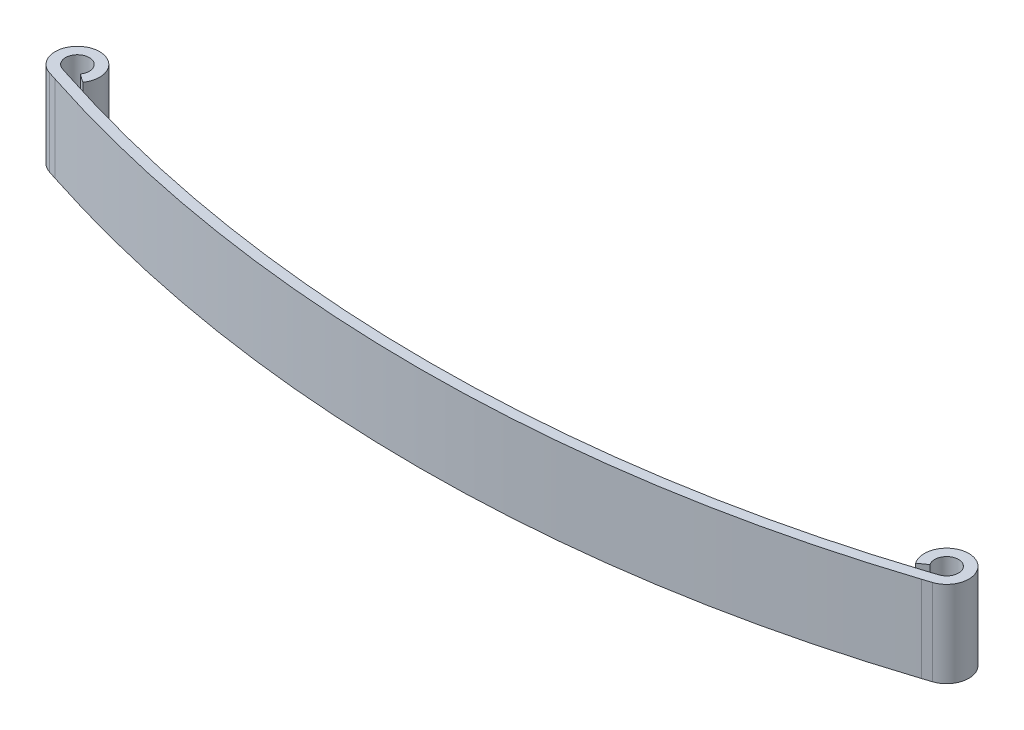
SolidWorks part; units mm, degrees
material "51 Si 7"
ref_plane "Ön Düzlem" through (0, 0, 0) normal (0, 0, 1) x (1, 0, 0)
ref_plane "Üst Düzlem" through (0, 0, 0) normal (0, 1, 0) x (1, 0, 0)
ref_plane "Sağ Düzlem" through (0, 0, 0) normal (1, 0, 0) x (0, 0, -1)
sketch "Sketch1" plane through (0, 0, 0) normal (0, 1, 0) x (1, 0, 0)
  line L0 (721.4563, -1539.3183) -> (730.9671, -1536.229)
  line L2 (725.1634, -1550.7313) -> (734.6743, -1547.642)
  line L4 (715.3996, -1531.0449) -> (705.5901, -1537.9567)
  line L5 (-282.2509, -1550.7313) -> (-291.7618, -1547.642)
  line L6 (-272.4871, -1531.0449) -> (-262.6775, -1537.9567)
  line L7 (-278.5437, -1539.3183) -> (-288.0546, -1536.229)
  arc A0 (-278.5437, -1539.3183) -> (721.4563, -1539.3183) centre (221.4563, 0) ccw
  arc A1 (-282.2509, -1550.7313) -> (725.1634, -1550.7313) centre (221.4563, 0) ccw
  arc A2 (730.9671, -1536.229) -> (715.3996, -1531.0449) centre (726.6975, -1523.0843) ccw
  arc A3 (734.6743, -1547.642) -> (705.5901, -1537.9567) centre (726.6975, -1523.0843) ccw
  arc A4 (-291.7618, -1547.642) -> (-262.6775, -1537.9567) centre (-283.7849, -1523.0843) cw
  arc A5 (-288.0546, -1536.229) -> (-272.4871, -1531.0449) centre (-283.7849, -1523.0843) cw
  circle A16 centre (221.4563, 0) radius 1630.4872 construction
  circle A17 centre (221.4563, 0) radius 1618.4872 construction
extrude "Boss-Extrude2" add sketch "Sketch1" along normal blind 100
